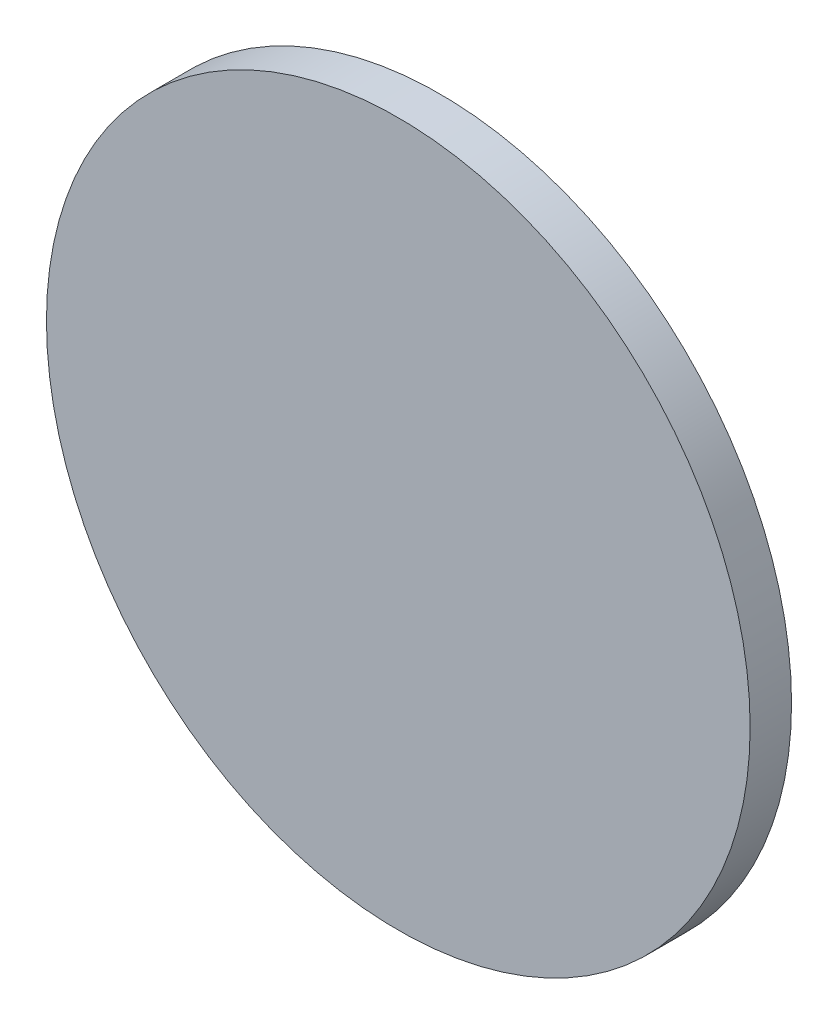
SolidWorks part; units mm, degrees
ref_plane "Plan de face" through (0, 0, 0) normal (0, 0, 1) x (1, 0, 0)
ref_plane "Plan de dessus" through (0, 0, 0) normal (0, 1, 0) x (1, 0, 0)
ref_plane "Plan de droite" through (0, 0, 0) normal (1, 0, 0) x (0, 0, -1)
sketch "Esquisse1" plane through (0, 0, 0) normal (0, 0, 1) x (1, 0, 0)
  circle A0 centre (24.65, 20) radius 4.25
extrude "Boss.-Extru.1" add sketch "Esquisse1" along normal up to surface (0.5 mm away)
